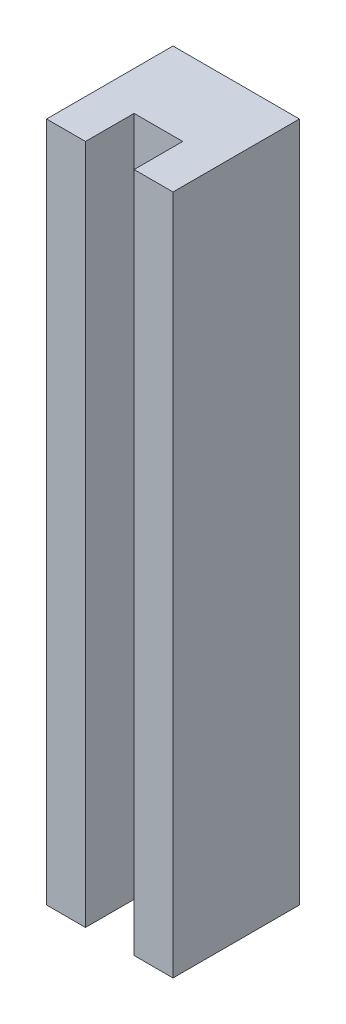
SolidWorks part; units mm, degrees
material "Brass"
ref_plane "Front Plane" through (0, 0, 0) normal (0, 0, 1) x (1, 0, 0)
ref_plane "Top Plane" through (0, 0, 0) normal (0, 1, 0) x (1, 0, 0)
ref_plane "Right Plane" through (0, 0, 0) normal (1, 0, 0) x (0, 0, -1)
sketch "Sketch1" plane through (0, 0, 0) normal (0, 1, 0) x (1, 0, 0)
  line L1 (0, 0) -> (6.5, 0)
  line L2 (0, 0) -> (0, -6.5)
  line L3 (0, -6.5) -> (6.5, -6.5)
  line L4 (6.5, 0) -> (6.5, -6.5)
  dimension "D1" = 6.5
  dimension "D2" = 6.5
extrude "Boss-Extrude1" add sketch "Sketch1" along normal blind 35
sketch "Sketch2" plane through (0, 35, 0) normal (0, 1, 0) x (1, 0, 0)
  line L0 (0, -6.5) -> (6.5, -6.5) construction
  line L1 (2, -6.5) -> (4.5, -6.5)
  line L2 (2, -6.5) -> (2, -4)
  line L3 (2, -4) -> (4.5, -4)
  line L4 (4.5, -6.5) -> (4.5, -4)
  point P6 (3.25, -6.5)
  point P7 (3.25, -4)
  dimension "D1" = 2.5
  dimension "D2" = 2.5
extrude "Cut-Extrude1" cut sketch "Sketch2" against normal through all both and the other way through all
